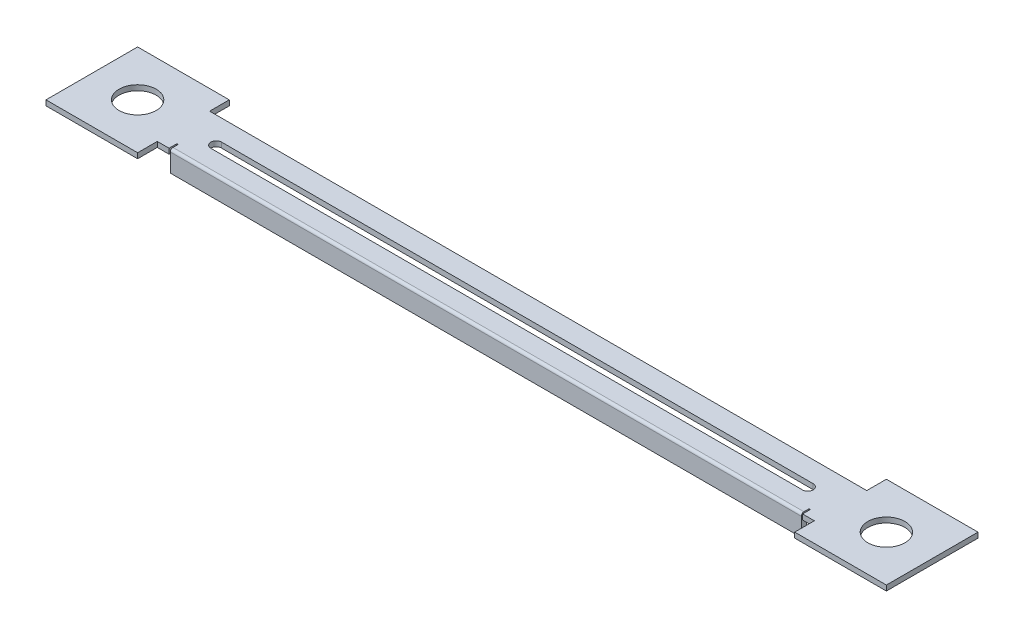
SolidWorks part; units mm, degrees
material "AISI 304"
ref_plane "Front Plane" through (0, 0, 0) normal (0, 0, 1) x (1, 0, 0)
ref_plane "Top Plane" through (0, 0, 0) normal (0, 1, 0) x (1, 0, 0)
ref_plane "Right Plane" through (0, 0, 0) normal (1, 0, 0) x (0, 0, -1)
sketch "Sketch1" plane through (0, 0, 0) normal (0, 1, 0) x (1, 0, 0)
  line L0 (0, 0) -> (286, 0) construction
  line L1 (143, 0) -> (143, 26.725) construction
  line L2 (-17.5, 17.5) -> (17.5, 17.5)
  line L3 (-17.5, 17.5) -> (-17.5, -17.5)
  line L4 (-17.5, -17.5) -> (17.5, -17.5)
  line L5 (17.5, 17.5) -> (17.5, 10)
  line L6 (-17.5, 17.5) -> (17.5, -17.5) construction
  line L7 (-17.5, -17.5) -> (17.5, 17.5) construction
  line L8 (303.5, -17.5) -> (268.5, -17.5)
  line L9 (268.5, 17.5) -> (268.5, 10)
  line L10 (303.5, 17.5) -> (268.5, 17.5)
  line L11 (303.5, 17.5) -> (303.5, -17.5)
  line L12 (17.5, 10) -> (268.5, 10)
  line L13 (17.5, -10) -> (268.5, -10)
  line L14 (17.5, -10) -> (17.5, -17.5)
  line L15 (268.5, -10) -> (268.5, -17.5)
  circle A0 centre (0, 0) radius 7.075
  circle A1 centre (286, 0) radius 7.075
  dimension "D2" = 14.15
  dimension "D3" = 14.15
  dimension "D1" = 286
  dimension "D4" = 35
  dimension "D5" = 35
  dimension "D6" = 10
extrude "Boss-Extrude1" add sketch "Sketch1" along normal blind 2
sketch "Sketch2" plane through (0, 0, 0) normal (0, -1, 0) x (1, 0, 0)
  line L1 (22.5, 8) -> (263.5, 8)
  line L2 (22.5, 10) -> (263.5, 10)
  line L4 (263.5, 10) -> (263.5, 8)
  line L5 (22.5, 10) -> (22.5, 8)
  line L6 (17.5, 17.5) -> (17.5, 10) construction
  line L7 (268.5, 10) -> (268.5, 17.5) construction
  line L8 (17.5, 10) -> (268.5, 10) construction
  dimension "D1" = 0
  dimension "D2" = 5
  dimension "D3" = 5
  dimension "D4" = 2
extrude "Boss-Extrude2" add sketch "Sketch2" along normal blind 6
sketch "Sketch3" plane through (0, 0, 10) normal (0, 0, 1) x (1, 0, 0)
  line L0 (22.5, 0) -> (22.5, 2)
  line L1 (17.5, 2) -> (268.5, 2) construction
  line L2 (22.5, 2) -> (22, 2)
  line L3 (22, 2) -> (22, 0)
  line L4 (17.5, 0) -> (22.5, 0) construction
  line L5 (22, 0) -> (22.5, 0)
  line L6 (143, 6.6664) -> (143, 2) construction
  line L7 (264, 2) -> (264, 0)
  line L8 (263.5, 2) -> (264, 2)
  line L9 (263.5, 0) -> (263.5, 2)
  line L10 (264, 0) -> (263.5, 0)
  dimension "D1" = 0.5
extrude "Cut-Extrude1" cut sketch "Sketch3" against normal blind 3
fillet "Fillet1" radius 1 1 edges at (143, 2, 10)
fillet "Fillet2" radius 0.7 1 edges at (143, 0, 8)
sketch "Sketch4" plane through (0, 0, 0) normal (0, -1, 0) x (1, 0, 0)
  line L0 (0, 0) -> (286, 0) construction
  line L1 (30, 0) -> (256, 0) construction
  line L2 (30, 2.05) -> (256, 2.05)
  line L3 (30, -2.05) -> (256, -2.05)
  arc A0 (30, 2.05) -> (30, -2.05) centre (30, 0) ccw
  arc A1 (256, -2.05) -> (256, 2.05) centre (256, 0) ccw
  point P6 (143, 0)
  dimension "D1" = 2.05
  dimension "D2" = 30
  dimension "D3" = 30
extrude "Cut-Extrude2" cut sketch "Sketch4" against normal through all
